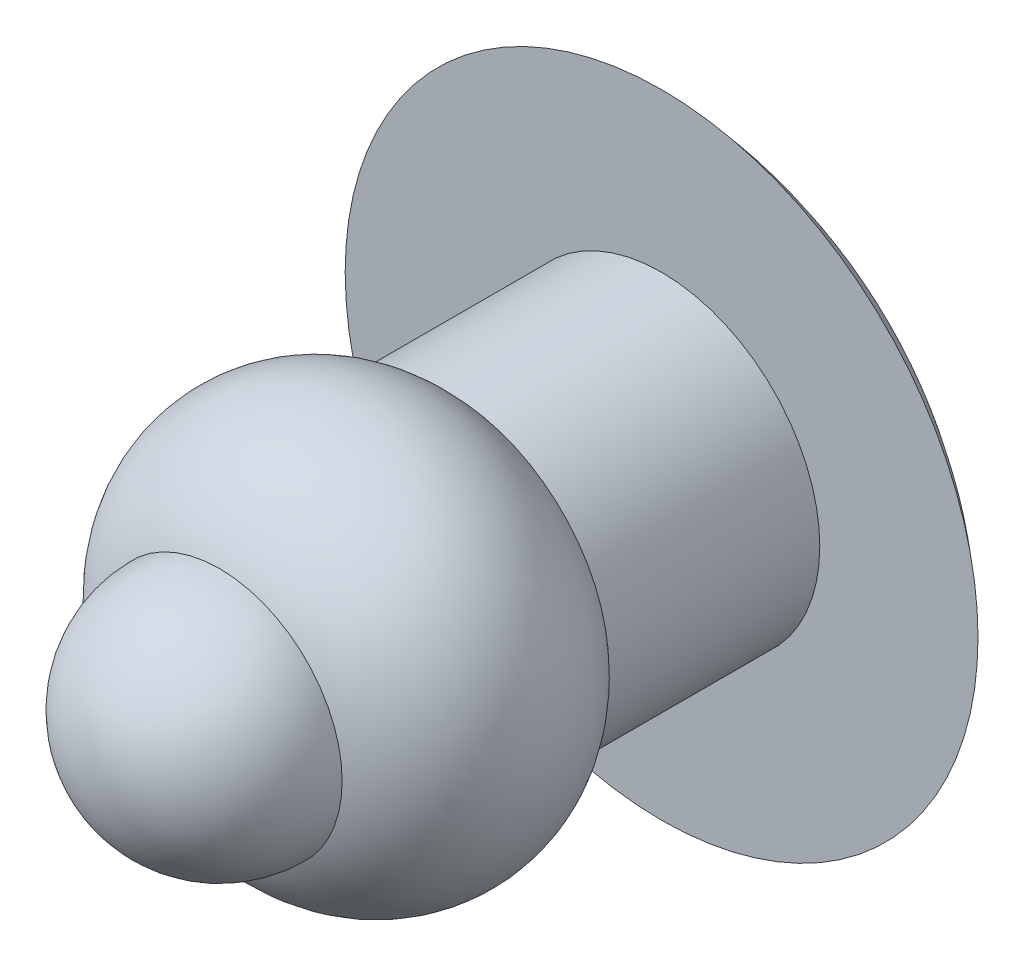
SolidWorks part; units mm, degrees
ref_plane "Front Plane" through (0, 0, 0) normal (0, 0, 1) x (1, 0, 0)
ref_plane "Top Plane" through (0, 0, 0) normal (0, 1, 0) x (1, 0, 0)
ref_plane "Right Plane" through (0, 0, 0) normal (1, 0, 0) x (0, 0, -1)
sketch "Sketch1" plane through (0, 0, 0) normal (1, 0, 0) x (0, 0, -1)
  line L0 (2.6127, 0) -> (-3.3552, 0) construction
  line L1 (0, 1.5) -> (2, 1.5)
  line L2 (2, 1.5) -> (2, 3)
  line L3 (3.0334, 1) -> (2.8334, 1)
  line L4 (2.8334, 1) -> (2.8334, 0)
  line L5 (-3.3552, 0) -> (2.8334, 0)
  arc A0 (3.0334, 1) -> (2, 3) centre (-1.3541, 0) ccw
  arc A2 (-2.1921, 1.1631) -> (-3.3552, 0) centre (-2.1921, 0) ccw
  arc A3 (0, 1.5) -> (-2.1921, 1.1631) centre (-0.9904, 0.6443) ccw
  dimension "D6" = 4.5
  dimension "D1" = 3
  dimension "D2" = 3
  dimension "D3" = 1
  dimension "D4" = 0.2
  dimension "D5" = 2
revolve "Revolve1" add sketch "Sketch1" angle 360 about L0
